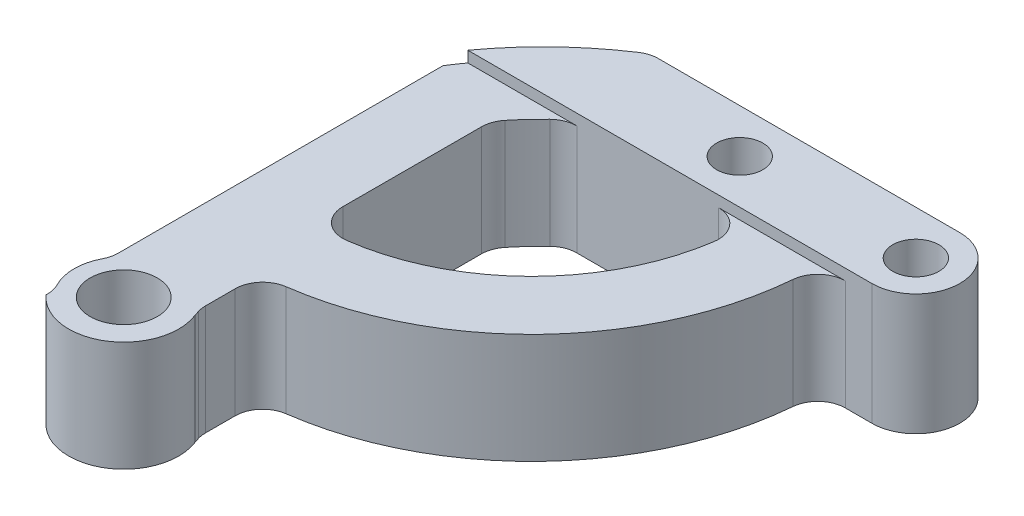
SolidWorks part; units mm, degrees
ref_plane "Front" through (0, 0, 0) normal (0, 0, 1) x (1, 0, 0)
ref_plane "Top" through (0, 0, 0) normal (0, 1, 0) x (1, 0, 0)
ref_plane "Right" through (0, 0, 0) normal (1, 0, 0) x (0, 0, -1)
sketch "Sketch1" plane through (0, 0, 0) normal (0, 1, 0) x (1, 0, 0)
  line L1 (-115.2537, -11) -> (-131.7843, -11)
  line L2 (-141.618, -48.4133) -> (-141.618, -47.6053)
  line L3 (-135.0594, -14.5432) -> (-135.0767, -30.6507)
  line L6 (-133.5072, -42.4283) -> (-133.5072, -37.0672)
  line L7 (-141.618, -42.5351) -> (-141.618, -12.3376)
  line L8 (-104, -3) -> (-132.1357, -3)
  line L9 (-104, -11) -> (-108.8005, -11)
  circle A26 centre (-104, -7) radius 2.1
  circle A27 centre (-120, -7) radius 2.1
  arc A32 (-104, -11) -> (-104, -3) centre (-104, -7) ccw
  arc A38 (-133.5072, -37.0672) -> (-108.8005, -11) centre (-134.9051, -11) ccw
  arc A40 (-132.1357, -3) -> (-141.618, -12.3376) centre (-115.9362, -28.9341) ccw
  arc A42 (-133.5072, -42.4283) -> (-133.2437, -43.2486) centre (0, 0) ccw
  arc A44 (-131.7843, -11) -> (-135.0594, -14.5432) centre (-115.9362, -28.9341) ccw
  arc A45 (-135.0767, -30.6507) -> (-115.2537, -11) centre (-134.9051, -11) ccw
  circle A50 centre (-137.9001, -45.0702) radius 3.05
  arc A51 (-141.618, -48.4133) -> (-133.2437, -43.2486) centre (-137.9001, -45.0702) ccw
  arc A54 (-141.618, -42.5351) -> (-141.618, -47.6053) centre (-137.9001, -45.0702) ccw
extrude "Boss-Extrude1" add sketch "Sketch1" along normal blind 11
fillet "Fillet1" radius 2.5 11 edges at (-132.1357, 5.5, 3) (-108.8005, 5.5, 11) (-135.0594, 5.5, 14.5432) (-135.0767, 5.5, 30.6507) (-115.2537, 5.5, 11) (-131.7843, 5.5, 11) (-133.5072, 5.5, 42.4283) (-133.5072, 5.5, 37.0672) (-133.2437, 5.5, 43.2486) (-141.618, 5.5, 47.6053) (-141.618, 5.5, 42.5351)
sketch "Sketch2" plane through (0, 11, 0) normal (0, 1, 0) x (1, 0, 0)
  line L0 (-106.4099, -11) -> (-104, -11) construction
  line L1 (-101.8, -11) -> (-164.6599, -11)
  line L2 (-101.8, -11) -> (-101.8, -78.1271)
  line L3 (-101.8, -78.1271) -> (-164.6599, -78.1271)
  line L4 (-164.6599, -11) -> (-164.6599, -78.1271)
  dimension "D1" = 0
extrude "Cut-Extrude1" cut sketch "Sketch2" against normal blind 1
